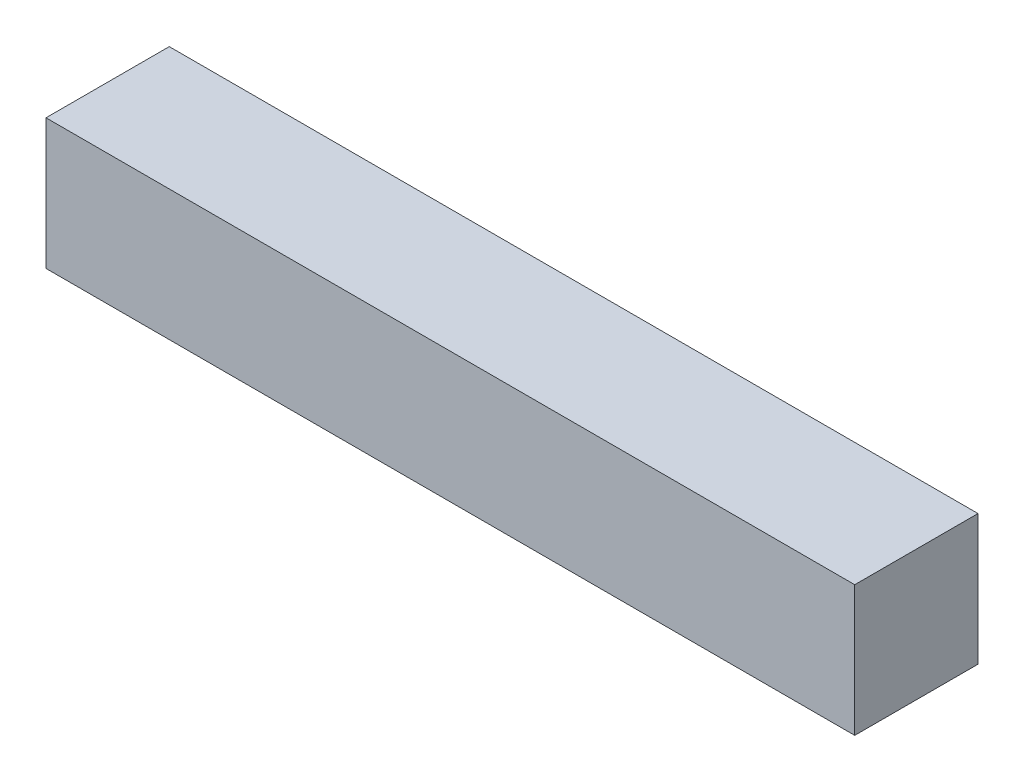
SolidWorks part; units mm, degrees
ref_plane "前视基准面" through (0, 0, 0) normal (0, 0, 1) x (1, 0, 0)
ref_plane "上视基准面" through (0, 0, 0) normal (0, 1, 0) x (1, 0, 0)
ref_plane "右视基准面" through (0, 0, 0) normal (1, 0, 0) x (0, 0, -1)
other "Configuration Table"
sketch "草图1" plane through (0, 0, 0) normal (1, 0, 0) x (0, 0, -1)
  line L1 (-36.1499, 40.063) -> (40.063, 40.063)
  line L2 (-36.1499, 40.063) -> (-36.1499, -40.622)
  line L3 (-36.1499, -40.622) -> (40.063, -40.622)
  line L4 (40.063, 40.063) -> (40.063, -40.622)
extrude "凸台-拉伸1" add sketch "草图1" along normal blind 500
